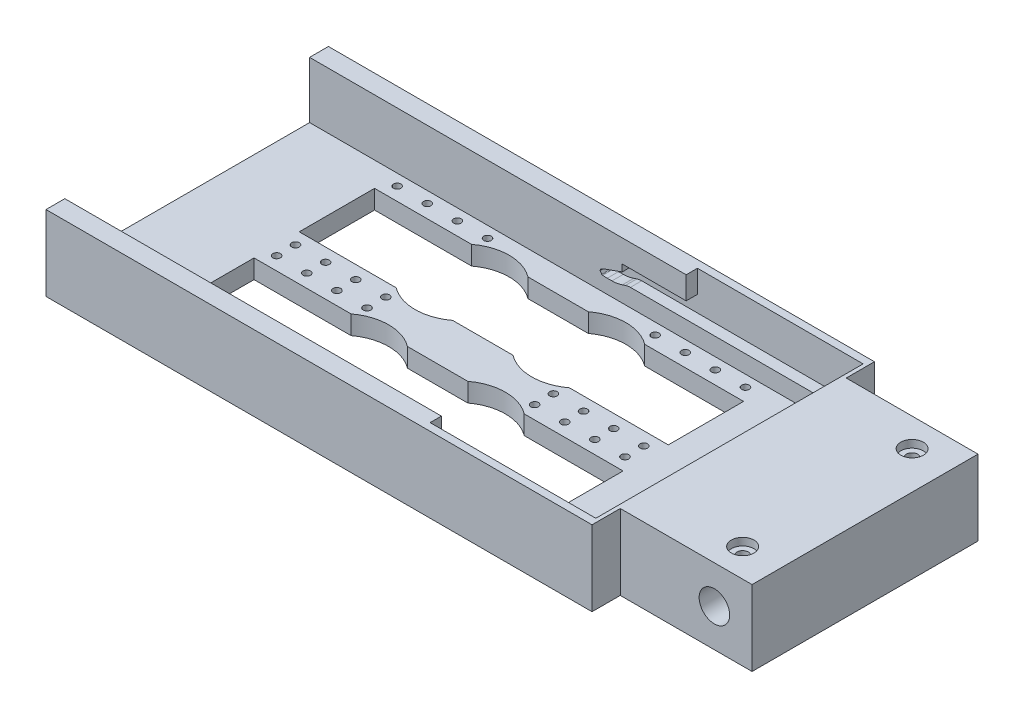
SolidWorks part; units mm, degrees
ref_plane "Front Plane" through (0, 0, 0) normal (0, 0, 1) x (1, 0, 0)
ref_plane "Top Plane" through (0, 0, 0) normal (0, 1, 0) x (1, 0, 0)
ref_plane "Right Plane" through (0, 0, 0) normal (1, 0, 0) x (0, 0, -1)
sketch "Sketch1" plane through (0, 0, 0) normal (0, 1, 0) x (1, 0, 0)
  line L1 (-90, 37.5) -> (90, 37.5)
  line L2 (-90, 37.5) -> (-90, -37.5)
  line L3 (-90, -37.5) -> (90, -37.5)
  line L4 (90, 37.5) -> (90, -37.5)
  line L5 (-90, 37.5) -> (90, -37.5) construction
  line L6 (-90, -37.5) -> (90, 37.5) construction
  circle A0 centre (80, 22.5) radius 1.5
  circle A1 centre (80, -22.5) radius 1.5
  point P0 (0, 0)
  dimension "D3" = 3
  dimension "D5" = 15
  dimension "D6" = 15
  dimension "D1" = 180
  dimension "D2" = 75
  dimension "D4" = 10
extrude "Boss-Extrude1" add sketch "Sketch1" along normal blind 20
sketch "Sketch2" plane through (0, 0, 37.5) normal (0, 0, 1) x (1, 0, 0)
  line L0 (90, 20) -> (90, 0) construction
  line L1 (-90, 20) -> (90, 20) construction
  line L2 (-90, 20) -> (40, 20) construction
  line L3 (-90, 20) -> (-90, 5) construction
  line L4 (-90, 5) -> (40, 5) construction
  line L5 (40, 20) -> (40, 5) construction
  line L6 (-90, 20) -> (40, 5) construction
  line L7 (-90, 5) -> (40, 20) construction
  line L8 (-90, 20) -> (-90, 0) construction
  circle A0 centre (80, 10) radius 4.05
  point P4 (90, 10)
  point P5 (-25, 12.5)
  dimension "D1" = 8.1
  dimension "D2" = 10
  dimension "D3" = 15
  dimension "D4" = 130
extrude "Cut-Extrude1" cut sketch "Sketch2" against normal through all
sketch "Sketch3" plane through (0, 20, 0) normal (0, 1, 0) x (1, 0, 0)
  line L2 (-63.75, 29.5) -> (-55.75, 29.5) construction
  line L3 (-63.75, 2.5) -> (-55.75, 2.5) construction
  line L4 (0, 0) -> (13.7346, 0) construction
  line L5 (90, -37.5) -> (90, 37.5) construction
  line L6 (4.75, 29.5) -> (12.75, 29.5) construction
  line L7 (-63.75, 29.5) -> (-63.75, 2.5) construction
  line L8 (-66.25, 26) -> (-40.5, 26)
  line L9 (-66.25, 26) -> (-66.25, 6)
  line L10 (-66.25, 6) -> (-40.5, 6)
  line L11 (31.75, 26) -> (31.75, 6)
  line L12 (4.75, 2.5) -> (12.75, 2.5) construction
  line L13 (4.75, -2.5) -> (12.75, -2.5) construction
  line L14 (-63.75, -29.5) -> (-63.75, -2.5) construction
  line L15 (4.75, -29.5) -> (12.75, -29.5) construction
  line L16 (-63.75, -2.5) -> (-55.75, -2.5) construction
  line L17 (-63.75, -29.5) -> (-55.75, -29.5) construction
  line L18 (31.75, -26) -> (31.75, -6)
  line L19 (-66.25, -6) -> (-40.5, -6)
  line L20 (-66.25, -26) -> (-66.25, -6)
  line L21 (-66.25, -26) -> (-40.5, -26)
  line L22 (-25.5, 6) -> (-9.5, 6)
  line L23 (-25.5, 26) -> (-9.5, 26)
  line L24 (5.5, 26) -> (31.75, 26)
  line L25 (5.5, 6) -> (31.75, 6)
  line L26 (-25.5, -6) -> (-9.5, -6)
  line L27 (-25.5, -26) -> (-9.5, -26)
  line L28 (5.5, -6) -> (31.75, -6)
  line L29 (5.5, -26) -> (31.75, -26)
  circle A0 centre (-63.75, 29.5) radius 1
  circle A1 centre (-63.75, 2.5) radius 1
  circle A2 centre (-55.75, 29.5) radius 1
  circle A3 centre (-47.75, 29.5) radius 1
  circle A4 centre (-39.75, 29.5) radius 1
  circle A11 centre (-55.75, 2.5) radius 1
  circle A12 centre (-47.75, 2.5) radius 1
  circle A13 centre (-39.75, 2.5) radius 1
  circle A50 centre (4.75, 29.5) radius 1
  circle A51 centre (4.75, 2.5) radius 1
  circle A52 centre (12.75, 29.5) radius 1
  circle A53 centre (20.75, 29.5) radius 1
  circle A54 centre (28.75, 29.5) radius 1
  circle A55 centre (12.75, 2.5) radius 1
  circle A56 centre (20.75, 2.5) radius 1
  circle A57 centre (28.75, 2.5) radius 1
  circle A58 centre (28.75, -2.5) radius 1
  circle A59 centre (20.75, -2.5) radius 1
  circle A60 centre (12.75, -2.5) radius 1
  circle A61 centre (28.75, -29.5) radius 1
  circle A62 centre (20.75, -29.5) radius 1
  circle A63 centre (12.75, -29.5) radius 1
  circle A64 centre (4.75, -2.5) radius 1
  circle A65 centre (4.75, -29.5) radius 1
  circle A66 centre (-39.75, -2.5) radius 1
  circle A67 centre (-47.75, -2.5) radius 1
  circle A68 centre (-55.75, -2.5) radius 1
  circle A69 centre (-39.75, -29.5) radius 1
  circle A70 centre (-47.75, -29.5) radius 1
  circle A71 centre (-55.75, -29.5) radius 1
  circle A72 centre (-63.75, -2.5) radius 1
  circle A73 centre (-63.75, -29.5) radius 1
  arc A74 (-40.5, 6) -> (-25.5, 6) centre (-33, 16) ccw
  arc A75 (-9.5, 6) -> (5.5, 6) centre (-2, 16) ccw
  arc A76 (-9.5, -26) -> (5.5, -26) centre (-2, -16) ccw
  arc A77 (-40.5, -26) -> (-25.5, -26) centre (-33, -16) ccw
  arc A78 (-25.5, 26) -> (-40.5, 26) centre (-33, 16) ccw
  arc A79 (5.5, 26) -> (-9.5, 26) centre (-2, 16) ccw
  arc A80 (-25.5, -6) -> (-40.5, -6) centre (-33, -16) ccw
  arc A81 (5.5, -6) -> (-9.5, -6) centre (-2, -16) ccw
  point P9 (-61.75, 6)
  point P96 (-66.25, 16)
  point P97 (-63.75, 16)
  dimension "D1" = 2
  dimension "D3" = 5
  dimension "D4" = 27
  dimension "D12" = 2
  dimension "D18" = 33.75
  dimension "D19" = 25
  dimension "D6" = 8
  dimension "D8" = 8
  dimension "D9" = 20
  dimension "D10" = 98
  dimension "D11" = 92
  dimension "D13" = 44.5
  dimension "D15" = 8
  dimension "D17" = 8
  dimension "D20" = 10
  dimension "D21" = 10
  dimension "D22" = 6.75
  dimension "D23" = 6.75
  dimension "D5" = 4
  dimension "D7" = 4
  dimension "D14" = 4
  dimension "D16" = 4
extrude "Cut-Extrude2" cut sketch "Sketch3" against normal through all
sketch "Sketch6" plane through (0, 20, 0) normal (0, 1, 0) x (1, 0, 0)
  line L0 (-90, -37.5) -> (90, -37.5) construction
  line L1 (55, 37.5) -> (90, 37.5)
  line L2 (55, 37.5) -> (55, 30)
  line L3 (55, 30) -> (90, 30)
  line L4 (90, 37.5) -> (90, 30)
  line L5 (55, 37.5) -> (90, 30) construction
  line L6 (55, 30) -> (90, 37.5) construction
  line L7 (55, -30) -> (90, -30)
  line L8 (55, -30) -> (55, -37.5)
  line L9 (55, -37.5) -> (90, -37.5)
  line L10 (90, -30) -> (90, -37.5)
  line L11 (55, -30) -> (90, -37.5) construction
  line L12 (55, -37.5) -> (90, -30) construction
  line L14 (90, -37.5) -> (90, 37.5) construction
  line L15 (90, 37.5) -> (-90, 37.5) construction
  point P0 (72.5, 33.75)
  point P5 (72.5, -33.75)
  dimension "D1" = 60
  dimension "D2" = 35
extrude "Cut-Extrude3" cut sketch "Sketch6" against normal through all
sketch "Sketch7" plane through (0, 20, 0) normal (0, 1, 0) x (1, 0, 0)
  line L0 (-90, 37.5) -> (-90, -37.5) construction
  line L1 (-90, 32.5) -> (50, 32.5)
  line L2 (-90, 32.5) -> (-90, -32.5)
  line L3 (-90, -32.5) -> (50, -32.5)
  line L4 (50, 32.5) -> (50, -32.5)
  line L5 (-90, 32.5) -> (50, -32.5) construction
  line L6 (-90, -32.5) -> (50, 32.5) construction
  point P0 (-20, 0)
  dimension "D1" = 65
  dimension "D2" = 140
extrude "Cut-Extrude4" cut sketch "Sketch7" against normal blind 15
sketch "Sketch8" plane through (0, 0, 0) normal (0, 0, 1) x (1, 0, 0)
  line L0 (60, 8.73) -> (-110.2739, 8.73) construction
  line L1 (-90, 0) -> (55, 0) construction
  line L2 (15.8524, 13.8221) -> (23, 14.1931)
  line L3 (15.8524, 13.8221) -> (-5.4943, 12.7138)
  line L4 (55, 0) -> (55, 20) construction
  line L5 (15.943, 11.0473) -> (54, 12.9563)
  line L6 (23, 14.1931) -> (23, 20)
  line L7 (-90, 20) -> (55, 20) construction
  line L8 (23, 20) -> (54, 20)
  line L9 (54, 20) -> (54, 12.9563)
  line L10 (-4.7867, 10.0075) -> (15.943, 11.0473)
  line L11 (-11.571, 10.4956) -> (-7.0679, 12.3585)
  line L12 (-10.8715, 8.73) -> (-9.6129, 8.8054)
  line L13 (-12.794, 9.4393) -> (-12.355, 8.8431)
  line L14 (-12.8018, 9.4838) -> (-12.7342, 9.7139)
  line L15 (-12.4274, 10.0693) -> (-11.571, 10.4956)
  line L16 (-12.5392, 9.9849) -> (-12.6502, 9.8631)
  line L17 (-12.1674, 8.7403) -> (-12.0783, 8.7343)
  line L18 (-6.8748, 9.4125) -> (-6.0777, 9.7277)
  arc A0 (-12.5392, 9.9849) -> (-12.4274, 10.0693) centre (-12.2576, 9.7282) cw
  arc A1 (-12.0783, 8.7343) -> (-10.8715, 8.73) centre (-11.4408, 18.238) ccw
  arc A2 (-7.0679, 12.3585) -> (-5.4943, 12.7138) centre (-5.2473, 7.9577) cw
  arc A3 (-12.7342, 9.7139) -> (-12.6502, 9.8631) centre (-12.3687, 9.6064) cw
  arc A4 (-12.794, 9.4393) -> (-12.8018, 9.4838) centre (-12.7531, 9.4694) cw
  arc A5 (-12.355, 8.8431) -> (-12.1674, 8.7403) centre (-12.1504, 8.9937) ccw
  arc A6 (-9.6129, 8.8054) -> (-6.8748, 9.4125) centre (-10.1443, 17.6795) ccw
  arc A7 (-6.0777, 9.7277) -> (-4.7867, 10.0075) centre (-4.5831, 5.9486) cw
  line B0 (-5.4943, 12.7138) -> (15.8524, 13.8221) construction
  line B1 (-4.7867, 10.0075) -> (15.943, 11.0473) construction
  line B2 (16.7875, 12.9343) -> (16.7875, 11.9352) construction
  line B3 (-11.571, 10.4956) -> (-7.0679, 12.3585) construction
  line B4 (-6.8748, 9.4125) -> (-6.0777, 9.7277) construction
  line B5 (-10.8715, 8.73) -> (-9.6129, 8.8054) construction
  line B6 (-12.794, 9.4393) -> (-12.355, 8.8431) construction
  line B7 (-12.6502, 9.8631) -> (-12.5392, 9.9849) construction
  line B8 (-12.4274, 10.0693) -> (-11.571, 10.4956) construction
  line B9 (-12.8018, 9.4838) -> (-12.7342, 9.7139) construction
  line B10 (-12.1674, 8.7403) -> (-12.0783, 8.7343) construction
  arc B11 (16.7875, 12.9343) -> (15.8524, 13.8221) centre (15.8985, 12.9343) ccw construction
  arc B12 (16.7875, 11.9352) -> (15.943, 11.0473) centre (15.8985, 11.9352) cw construction
  arc B13 (-6.8748, 9.4125) -> (-9.6129, 8.8054) centre (-10.1443, 17.6795) cw construction
  arc B14 (-6.0777, 9.7277) -> (-4.7867, 10.0075) centre (-4.5831, 5.9486) cw construction
  arc B15 (-7.0679, 12.3585) -> (-5.4943, 12.7138) centre (-5.2473, 7.9577) cw construction
  arc B16 (-12.7342, 9.7139) -> (-12.6502, 9.8631) centre (-12.3687, 9.6064) cw construction
  arc B17 (-12.4274, 10.0693) -> (-12.5392, 9.9849) centre (-12.2576, 9.7282) ccw construction
  arc B18 (-12.8018, 9.4838) -> (-12.794, 9.4393) centre (-12.7531, 9.4694) ccw construction
  arc B19 (-12.1674, 8.7403) -> (-12.355, 8.8431) centre (-12.1504, 8.9937) cw construction
  arc B20 (-12.0783, 8.7343) -> (-10.8715, 8.73) centre (-11.4408, 18.238) ccw construction
  dimension "D1" = 8.73
  dimension "D2" = 38.2125
  dimension "D3" = 32
  dimension "D4" = 1
sketch_block_instance "ScanOutline-10"
sketch_block "ScanOutline" parameters "D1"=0.889, "D2"=8.89, "D3"=4.064, "D4"=4.7625, "D5"=0.381, "D6"=0.0508, "D7"=0.254, "D8"=9.525
extrude "Cut-Extrude5" [suppressed] cut sketch "Sketch8" against normal mid plane 72
sketch "Sketch9" plane through (0, 20, 0) normal (0, 1, 0) x (1, 0, 0)
  line L1 (90, 30) -> (55, 30)
  line L2 (90, 30) -> (90, -30)
  line L3 (90, -30) -> (55, -30)
  line L4 (55, 30) -> (55, -30)
extrude "Cut-Extrude6" [suppressed] cut sketch "Sketch9" against normal through all
sketch "Sketch10" plane through (0, 0, 0) normal (0, 0, 1) x (1, 0, 0)
  line L0 (59.917, 8.73) -> (-110.3568, 8.73) construction
  line L7 (-4.8133, 9.701) -> (15.9425, 9.701)
  line L8 (-11.5646, 10.5284) -> (-6.9739, 12.1634)
  line L9 (-10.9545, 8.73) -> (-9.6937, 8.7422)
  line L10 (-12.839, 9.5347) -> (-12.4304, 8.9173)
  line L11 (-12.8446, 9.5795) -> (-12.7655, 9.8059)
  line L12 (-12.4413, 10.1456) -> (-11.5646, 10.5284)
  line L13 (-12.5571, 10.0669) -> (-12.6742, 9.9508)
  line L14 (-12.2482, 8.8052) -> (-12.1596, 8.7948)
  line L15 (-6.9285, 9.2114) -> (-6.1167, 9.4863)
  line L16 (-90, 0) -> (55, 0) construction
  line L17 (15.9425, 9.701) -> (54, 9.701)
  line L19 (10, 13.9928) -> (-6.9739, 13.9928)
  line L20 (-6.9739, 13.9928) -> (-6.9739, 12.1634)
  line L21 (55, 0) -> (55, 20) construction
  line L22 (10, 13.9928) -> (10, 20)
  line L23 (-90, 20) -> (55, 20) construction
  line L24 (54, 20) -> (54, 9.701)
  line L25 (55, 0) -> (55, 20) construction
  line L26 (10, 20) -> (54, 20)
  arc A0 (-12.5571, 10.0669) -> (-12.4413, 10.1456) centre (-12.2888, 9.7964) cw
  arc A1 (-12.1596, 8.7948) -> (-10.9545, 8.73) centre (-11.0468, 18.2546) ccw
  arc A3 (-12.7655, 9.8059) -> (-12.6742, 9.9508) centre (-12.4058, 9.6803) cw
  arc A4 (-12.839, 9.5347) -> (-12.8446, 9.5795) centre (-12.7967, 9.5628) cw
  arc A5 (-12.4304, 8.9173) -> (-12.2482, 8.8052) centre (-12.2186, 9.0575) ccw
  arc A6 (-9.6937, 8.7422) -> (-6.9285, 9.2114) centre (-9.7798, 17.6318) ccw
  arc A7 (-6.1167, 9.4863) -> (-4.8133, 9.701) centre (-4.8133, 5.637) cw
  point P4 (0, 0)
  point P10 (0, 0)
  line B0 (-5.3844, 12.4394) -> (15.991, 12.4768) construction
  line B1 (-4.8133, 9.701) -> (15.9425, 9.701) construction
  line B2 (16.8804, 11.5433) -> (16.8304, 10.5455) construction
  line B3 (-11.5646, 10.5284) -> (-6.9739, 12.1634) construction
  line B4 (-6.9285, 9.2114) -> (-6.1167, 9.4863) construction
  line B5 (-10.9545, 8.73) -> (-9.6937, 8.7422) construction
  line B6 (-12.839, 9.5347) -> (-12.4304, 8.9173) construction
  line B7 (-12.6742, 9.9508) -> (-12.5571, 10.0669) construction
  line B8 (-12.4413, 10.1456) -> (-11.5646, 10.5284) construction
  line B9 (-12.8446, 9.5795) -> (-12.7655, 9.8059) construction
  line B10 (-12.2482, 8.8052) -> (-12.1596, 8.7948) construction
  arc B11 (16.8804, 11.5433) -> (15.991, 12.4768) centre (15.9926, 11.5878) ccw construction
  arc B12 (16.8304, 10.5455) -> (15.9425, 9.701) centre (15.9425, 10.59) cw construction
  arc B13 (-6.9285, 9.2114) -> (-9.6937, 8.7422) centre (-9.7798, 17.6318) cw construction
  arc B14 (-6.1167, 9.4863) -> (-4.8133, 9.701) centre (-4.8133, 5.637) cw construction
  arc B15 (-6.9739, 12.1634) -> (-5.3844, 12.4394) centre (-5.3761, 7.6769) cw construction
  arc B16 (-12.7655, 9.8059) -> (-12.6742, 9.9508) centre (-12.4058, 9.6803) cw construction
  arc B17 (-12.4413, 10.1456) -> (-12.5571, 10.0669) centre (-12.2888, 9.7964) ccw construction
  arc B18 (-12.8446, 9.5795) -> (-12.839, 9.5347) centre (-12.7967, 9.5628) ccw construction
  arc B19 (-12.2482, 8.8052) -> (-12.4304, 8.9173) centre (-12.2186, 9.0575) cw construction
  arc B20 (-12.1596, 8.7948) -> (-10.9545, 8.73) centre (-11.0468, 18.2546) ccw construction
  dimension "D1" = 8.73
  dimension "D3" = 39.0575
  dimension "D4" = 1
  dimension "D5" = 45
  dimension "D6" = 1.8294
sketch_block_instance "ScanOutline-14"
sketch "Sketch11" plane through (0, 20, 0) normal (0, 1, 0) x (1, 0, 0)
  circle A0 centre (80, 22.5) radius 3
  circle A1 centre (80, -22.5) radius 3
  dimension "D1" = 6
  dimension "D2" = 6
extrude "Cut-Extrude7" cut sketch "Sketch11" against normal blind 2
extrude "Cut-Extrude8" cut sketch "Sketch10" against normal mid plane 71 contours L7 L17 L24 L26 L22 L19 L20 L8 L12 A0 L13 A3 L11 A4 L10 A5 L14 A1 L9 A6 L15 A7
